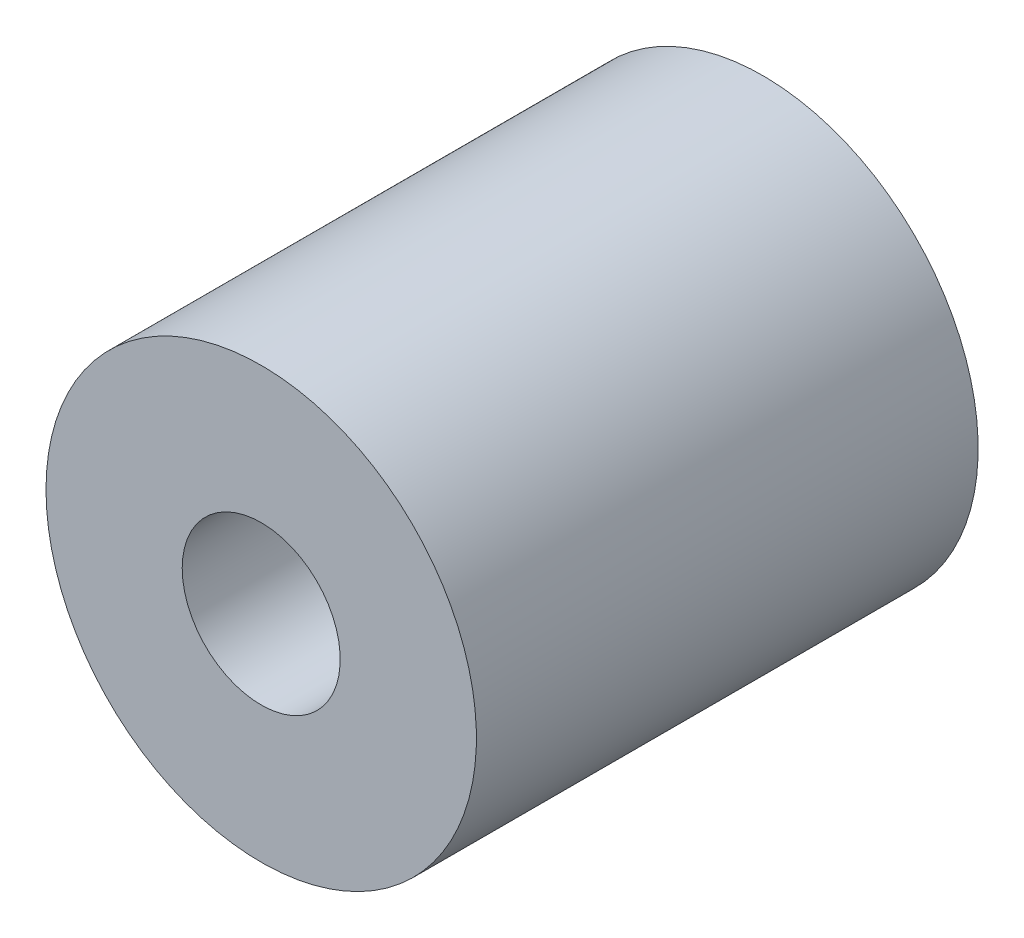
SolidWorks part; units mm, degrees
material "6061-T6 (SS)"
ref_plane "Front Plane" through (0, 0, 0) normal (0, 0, 1) x (1, 0, 0)
ref_plane "Top Plane" through (0, 0, 0) normal (0, 1, 0) x (1, 0, 0)
ref_plane "Right Plane" through (0, 0, 0) normal (1, 0, 0) x (0, 0, -1)
sketch "Sketch1" plane through (0, 0, 0) normal (1, 0, 0) x (0, 0, -1)
  line L0 (21.7309, 0) -> (-28.9169, 0) construction
  line L1 (-10.3632, 8.89) -> (-10.3632, 3.2639)
  line L2 (-10.3632, 8.89) -> (10.3632, 8.89)
  line L3 (-10.3632, 3.2639) -> (10.3632, 3.2639)
  line L4 (10.3632, 8.89) -> (10.3632, 3.2639)
  point P3 (0, 3.2639)
  dimension "D1" = 17.78
  dimension "D2" = 6.5278
  dimension "D3" = 20.7264
revolve "Revolve1" add sketch "Sketch1" angle 360 about L0
